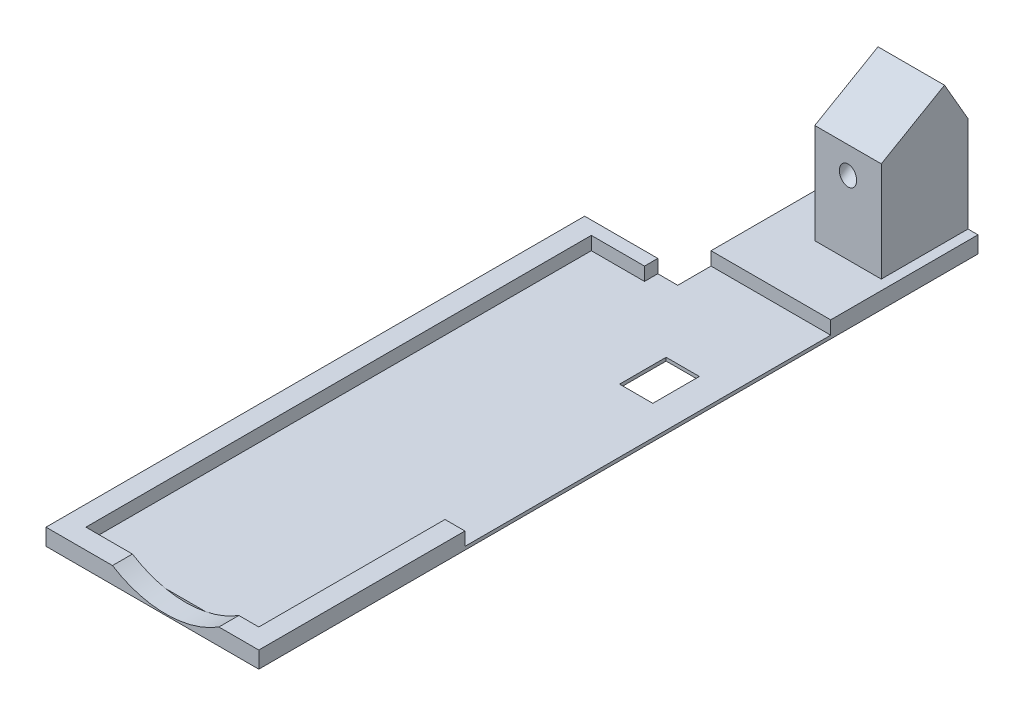
SolidWorks part; units mm, degrees
ref_plane "Front Plane" through (0, 0, 0) normal (0, 0, 1) x (1, 0, 0)
ref_plane "Top Plane" through (0, 0, 0) normal (0, 1, 0) x (1, 0, 0)
ref_plane "Right Plane" through (0, 0, 0) normal (1, 0, 0) x (0, 0, -1)
sketch "Sketch1" plane through (0, 0, 0) normal (1, 0, 0) x (0, 0, -1)
  line L1 (19.1061, 15.0102) -> (28.6147, 20.5)
  line L2 (28.6147, 20.5) -> (32.1497, 14.3772)
  line L19 (32.1497, 14.3772) -> (32.1497, 0)
  line L20 (32.1497, 0) -> (19.1061, 0)
  line L21 (19.1061, 15.0102) -> (19.1061, 0)
  dimension "D1" = 10.9796
  dimension "D2" = 15.0102
  dimension "D3" = 7.07
  dimension "D4" = 14.3772
  dimension "D5" = 19.1061
extrude "Boss-Extrude1" add sketch "Sketch1" along normal blind 10
sketch "Sketch2" plane through (0, 17.5155, -30.3378) normal (0, 0.5, -0.866) x (1, 0, 0)
  line L1 (10, -3.4462) -> (0, -3.4462) construction
  circle A0 centre (5, 0.0538) radius 1.75
  dimension "D1" = 3.5
  dimension "D2" = 5
  dimension "D3" = 3.5
extrude "Cut-Extrude1" cut sketch "Sketch2" against normal blind 35
draft "Draft1" type of draft neutral plane draft angle 2 faces to draft 1 face at (5, 18.9845, -29.4897) neutral plane through (10, 20.5, -28.6147) neutral plane normal (0, 0.5, -0.866) parameters "D1"=2
sketch "Sketch5" plane through (0, 0, 0) normal (0, -1, 0) x (1, 0, 0)
  line L2 (11.5, 76) -> (-20.5, 76)
  line L4 (-20.5, -5) -> (-6.5, -5)
  line L12 (-20.5, -5) -> (-20.5, 76)
  line L17 (-6.5, -32.15) -> (11.5, -32.15)
  line L18 (0, -19.1061) -> (0, -32.1497) construction
  line L19 (11.5, -32.15) -> (11.5, 76)
  line L20 (-6.5, -5) -> (-6.5, -32.15)
  dimension "D1" = 32
  dimension "D2" = 108.15
  dimension "D3" = 14
  dimension "D4" = 5
  dimension "D5" = 81
  dimension "D6" = 6.5
extrude "Boss-Extrude2" add sketch "Sketch5" along normal blind 2.5
sketch "Sketch6" plane through (0, 0, 0) normal (0, 1, 0) x (1, 0, 0)
  line L10 (8.5, 3) -> (-17.5, 3)
  line L12 (8.5, 3) -> (8.5, -73)
  line L13 (8.5, -73) -> (-17.5, -73)
  line L14 (-17.5, 3) -> (-17.5, -73)
  line L15 (8.5, 3) -> (-17.5, -73) construction
  line L16 (8.5, -73) -> (-17.5, 3) construction
  point P0 (-4.5, -35)
  dimension "D1" = 26
  dimension "D2" = 3
  dimension "D3" = 17.5
  dimension "D4" = 76
extrude "Cut-Extrude4" cut sketch "Sketch6" against normal blind 2
sketch "Sketch7" plane through (0, -2, 0) normal (0, 1, 0) x (1, 0, 0)
  line L1 (2, -5.25) -> (7, -5.25)
  line L2 (2, -5.25) -> (2, -12.25)
  line L3 (2, -12.25) -> (7, -12.25)
  line L4 (7, -5.25) -> (7, -12.25)
  line L5 (2, -5.25) -> (7, -12.25) construction
  line L6 (2, -12.25) -> (7, -5.25) construction
  line L8 (8.5, -73) -> (8.5, 3) construction
  line L9 (8.5, 3) -> (-17.5, 3) construction
  point P0 (4.5, -8.75)
  dimension "D1" = 7
  dimension "D2" = 5
  dimension "D3" = 4
  dimension "D4" = 11.75
extrude "Cut-Extrude5" cut sketch "Sketch7" against normal blind 1
sketch "Sketch8" plane through (0, 0, 73) normal (0, 0, -1) x (-1, 0, 0)
  line L0 (20.5, 0) -> (6.5, 0) construction
  line L1 (-5.5, 0) -> (10.5, 0)
  arc A0 (10.5, 0) -> (-5.5, 0) centre (2.5, 12.6886) cw
  dimension "D2" = 15
  dimension "D1" = 16
  dimension "D3" = 10.5
extrude "Cut-Extrude6" cut sketch "Sketch8" against normal blind 5
sketch "Sketch9" plane through (0, 0, 0) normal (0, 1, 0) x (1, 0, 0)
  line L0 (11.5, 32.15) -> (11.5, -76) construction
  line L5 (11.5, 10) -> (-9.5, 10)
  line L6 (11.5, 10) -> (11.5, -45)
  line L7 (11.5, -45) -> (-9.5, -45)
  line L8 (-9.5, 10) -> (-9.5, -45)
  dimension "D1" = 21
  dimension "D2" = 55
  dimension "D3" = 10
extrude "Cut-Extrude7" cut sketch "Sketch9" against normal blind 2
